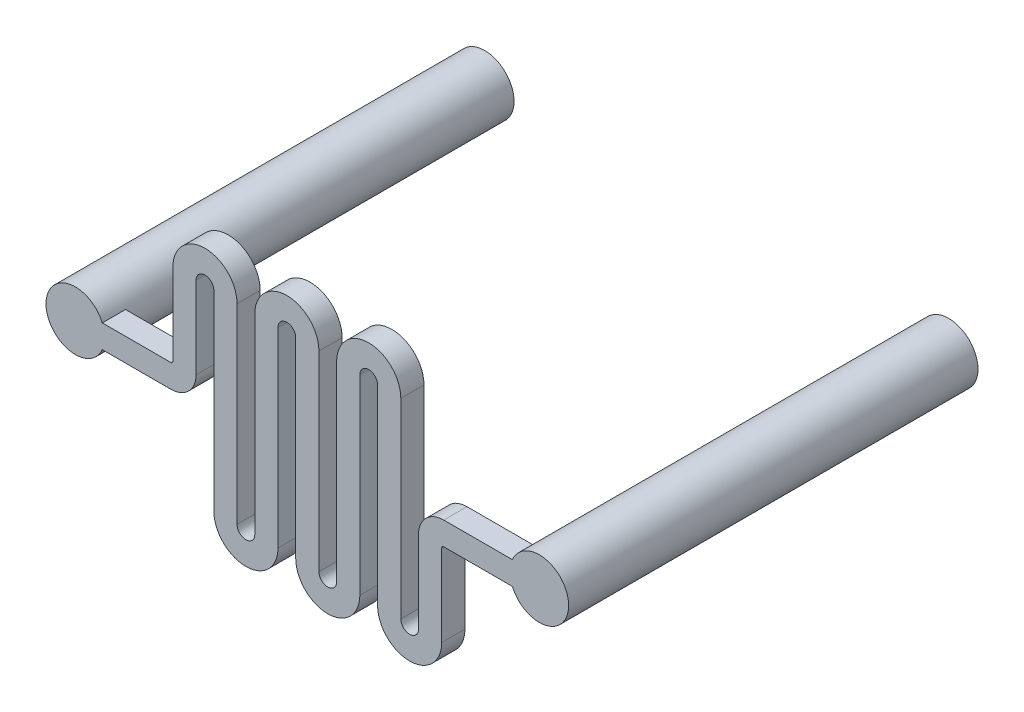
SolidWorks part; units mm, degrees
ref_plane "Front Plane" through (0, 0, 0) normal (0, 0, 1) x (1, 0, 0)
ref_plane "Top Plane" through (0, 0, 0) normal (0, 1, 0) x (1, 0, 0)
ref_plane "Right Plane" through (0, 0, 0) normal (1, 0, 0) x (0, 0, -1)
sketch "Sketch2" plane through (0, 0, 0) normal (0, 0, 1) x (1, 0, 0)
  line L3 (-20.5, -0.85) -> (-13.5, -0.85)
  line L6 (-11.65, 1) -> (-11.65, 7)
  line L9 (-10.35, 7) -> (-10.35, 0)
  line L12 (-10.35, 0) -> (-10.35, -7)
  line L15 (-5.65, -7) -> (-5.65, 0)
  line L18 (-5.65, 0) -> (-5.65, 7)
  line L21 (-4.35, 7) -> (-4.35, 0)
  line L22 (-4.35, 0) -> (-4.35, -7)
  line L23 (0.35, -7) -> (0.35, 0)
  line L24 (0.35, 0) -> (0.35, 7)
  line L25 (1.65, 7) -> (1.65, 0)
  line L26 (1.65, 0) -> (1.65, -7)
  line L27 (6.35, -7) -> (6.35, -1)
  line L28 (6.5, -0.85) -> (13.5, -0.85)
  line L29 (-20.5, 0.85) -> (-13.5, 0.85)
  line L30 (-13.35, 1) -> (-13.35, 7)
  line L31 (-8.65, 7) -> (-8.65, 0)
  line L32 (-8.65, 0) -> (-8.65, -7)
  line L33 (-7.35, -7) -> (-7.35, 0)
  line L34 (-7.35, 0) -> (-7.35, 7)
  line L35 (-2.65, 7) -> (-2.65, 0)
  line L36 (-2.65, 0) -> (-2.65, -7)
  line L37 (-1.35, -7) -> (-1.35, 0)
  line L38 (-1.35, 0) -> (-1.35, 7)
  line L39 (3.35, 7) -> (3.35, 0)
  line L40 (3.35, 0) -> (3.35, -7)
  line L41 (4.65, -7) -> (4.65, -1)
  line L42 (6.5, 0.85) -> (13.5, 0.85)
  arc A8 (-11.65, 1) -> (-13.5, -0.85) centre (-13.5, 1) cw
  arc A9 (-11.65, 7) -> (-10.35, 7) centre (-11, 7) cw
  arc A10 (-10.35, -7) -> (-5.65, -7) centre (-8, -7) ccw
  arc A11 (-5.65, 7) -> (-4.35, 7) centre (-5, 7) cw
  arc A12 (-4.35, -7) -> (0.35, -7) centre (-2, -7) ccw
  arc A13 (0.35, 7) -> (1.65, 7) centre (1, 7) cw
  arc A14 (1.65, -7) -> (6.35, -7) centre (4, -7) ccw
  arc A15 (6.35, -1) -> (6.5, -0.85) centre (6.5, -1) cw
  arc A16 (-13.35, 1) -> (-13.5, 0.85) centre (-13.5, 1) cw
  arc A17 (-13.35, 7) -> (-8.65, 7) centre (-11, 7) cw
  arc A18 (-8.65, -7) -> (-7.35, -7) centre (-8, -7) ccw
  arc A19 (-7.35, 7) -> (-2.65, 7) centre (-5, 7) cw
  arc A20 (-2.65, -7) -> (-1.35, -7) centre (-2, -7) ccw
  arc A21 (-1.35, 7) -> (3.35, 7) centre (1, 7) cw
  arc A22 (3.35, -7) -> (4.65, -7) centre (4, -7) ccw
  arc A23 (4.65, -1) -> (6.5, 0.85) centre (6.5, -1) cw
  arc A24 (-20.5, 0.85) -> (-20.5, -0.85) centre (-20.5, 0) ccw
  arc A25 (13.5, -0.85) -> (13.5, 0.85) centre (13.5, 0) ccw
  point P4 (0, 0)
  point P32 (5.5, 0)
  point P35 (-12.5, 0)
  dimension "D14" = 8
extrude "Boss-Extrude1" add sketch "Sketch2" along normal blind 1.7
ref_plane "Plane1" through (0, 0, 0) normal (0, 1, 0) x (1, 0, 0)
ref_plane "Plane2" through (0, 0, 0) normal (0, 1, 0) x (1, 0, 0)
sketch "Sketch3" plane through (0, 0, 0) normal (0, 1, 0) x (1, 0, 0)
  line L1 (-20.5, 28.3) -> (-22.65, 28.3)
  line L2 (-20.5, -1.7) -> (-20.5, 28.3)
  line L6 (-22.65, 28.3) -> (-22.65, -1.7)
  line L7 (-22.65, -1.7) -> (-20.5, -1.7)
  dimension "D1" = 2.15
  dimension "D3" = 30
sketch "Sketch4" plane through (0, 0, 0) normal (0, 1, 0) x (1, 0, 0)
  line L1 (13.5, 28.3) -> (15.65, 28.3)
  line L2 (13.5, -1.7) -> (13.5, 28.3)
  line L6 (15.65, 28.3) -> (15.65, -1.7)
  line L7 (15.65, -1.7) -> (13.5, -1.7)
  dimension "D1" = 2.15
  dimension "D4" = 30
revolve "Revolve1" add sketch "Sketch3" angle 360 about L2
revolve "Revolve2" add sketch "Sketch4" angle 360 about L2
sketch "Sketch5" plane through (0, 0, -28.3) normal (0, 0, -1) x (-1, 0, 0)
  circle A0 centre (-13.5, 0) radius 1.5
  circle A1 centre (20.5, 0) radius 1.5
  dimension "D1" = 3
  dimension "D2" = 3
extrude "Cut-Extrude1" cut sketch "Sketch5" against normal blind 28
